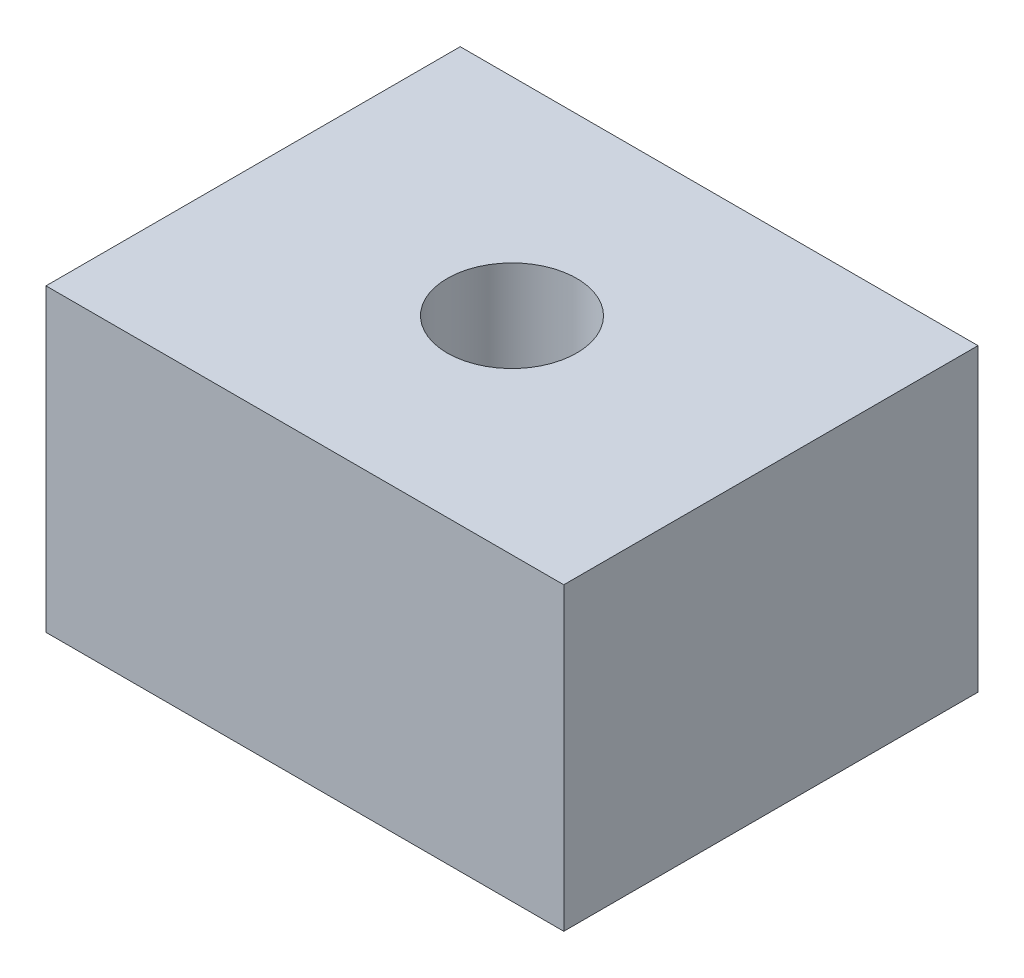
SolidWorks part; units mm, degrees
ref_plane "Front Plane" through (0, 0, 0) normal (0, 0, 1) x (1, 0, 0)
ref_plane "Top Plane" through (0, 0, 0) normal (0, 1, 0) x (1, 0, 0)
ref_plane "Right Plane" through (0, 0, 0) normal (1, 0, 0) x (0, 0, -1)
sketch "Sketch1" plane through (0, 0, 0) normal (0, 1, 0) x (1, 0, 0)
  line L1 (-12.7, -10.16) -> (12.7, -10.16)
  line L2 (-12.7, -10.16) -> (-12.7, 10.16)
  line L3 (-12.7, 10.16) -> (12.7, 10.16)
  line L4 (12.7, -10.16) -> (12.7, 10.16)
  line L5 (-12.7, -10.16) -> (12.7, 10.16) construction
  line L6 (-12.7, 10.16) -> (12.7, -10.16) construction
  circle A0 centre (0, 0) radius 3.175
  point P0 (0, 0)
  dimension "D1" = 20.32
  dimension "D2" = 25.4
extrude "Boss-Extrude1" add sketch "Sketch1" along normal blind 14.7225
